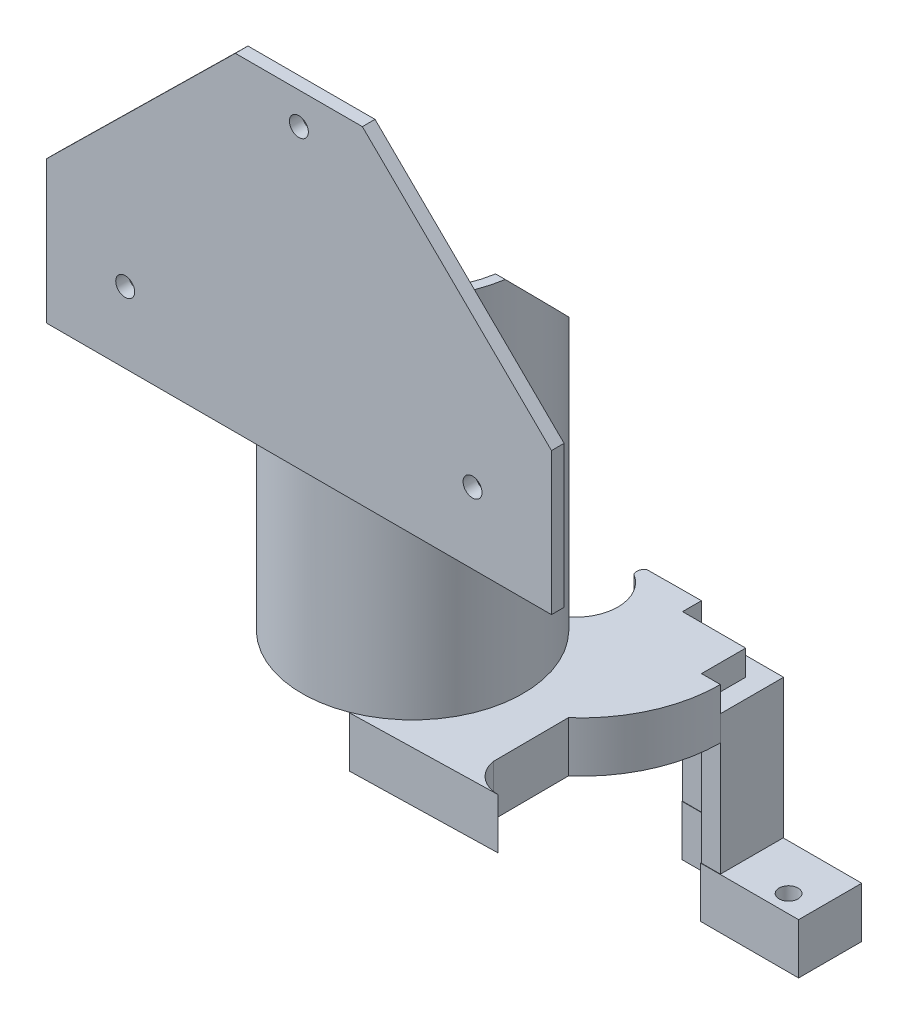
SolidWorks part; units mm, degrees
ref_plane "Front Plane" through (0, 0, 0) normal (0, 0, 1) x (1, 0, 0)
ref_plane "Top Plane" through (0, 0, 0) normal (0, 1, 0) x (1, 0, 0)
ref_plane "Right Plane" through (0, 0, 0) normal (1, 0, 0) x (0, 0, -1)
sketch "Sketch1" plane through (0, 0, 0) normal (0, 1, 0) x (1, 0, 0)
  circle A0 centre (0, 0) radius 17.5
  dimension "D1" = 35
extrude "Boss-Extrude1" add sketch "Sketch1" along normal blind 53 and the other way blind 5
sketch "Sketch2" plane through (0, 53, 0) normal (0, 1, 0) x (1, 0, 0)
  circle A0 centre (0, 0) radius 16
extrude "Cut-Extrude1" cut sketch "Sketch2" against normal blind 108
sketch "Sketch3" plane through (0, 53, 0) normal (0, 1, 0) x (1, 0, 0)
  line L1 (-12.5, 6) -> (12.5, 6)
  line L2 (-12.5, 6) -> (-12.5, 26)
  line L3 (-12.5, 26) -> (12.5, 26)
  line L4 (12.5, 6) -> (12.5, 26)
  line L5 (-12.5, 6) -> (12.5, 26) construction
  line L6 (-12.5, 26) -> (12.5, 6) construction
  circle A0 centre (0, 0) radius 16 construction
  point P0 (0, 16)
extrude "Cut-Extrude2" cut sketch "Sketch3" against normal blind 108
sketch "Sketch7" plane through (0, 0, 0) normal (1, 0, 0) x (0, 0, -1)
  line L0 (12.2474, 53) -> (12.2474, 38)
  line L1 (12.2474, -5) -> (12.2474, 53) construction
  line L2 (12.2474, 38) -> (-2.6263, 53)
  line L3 (12.2474, 53) -> (-17.5, 53) construction
  line L4 (-2.6263, 53) -> (12.2474, 53)
extrude "Cut-Extrude3" cut sketch "Sketch7" against normal blind 108 and the other way blind 108
ref_plane "Plane1" through (0, 0, 18) normal (0, 0, 1) x (1, 0, 0)
sketch "Sketch8" plane through (0, 0, 18) normal (0, 0, 1) x (1, 0, 0)
  line L1 (10.0571, 78.0232) -> (40, 48.5711)
  line L2 (40, 48.5711) -> (40, 26.0711)
  line L3 (40, 26.0711) -> (0, 26.0711)
  line L5 (0, -16.3611) -> (0, 16.3611) construction
  line L7 (-40, 26.0711) -> (0, 26.0711)
  line L8 (-40, 48.5711) -> (-40, 26.0711)
  line L9 (-10.0571, 78.0232) -> (-40, 48.5711)
  line L11 (-10.0571, 78.0232) -> (10.0571, 78.0232)
extrude "Boss-Extrude2" add sketch "Sketch8" against normal blind 2
sketch "Sketch10" plane through (0, 0, 16) normal (0, 0, -1) x (-1, 0, 0)
  line L0 (0, 53) -> (0, 73) construction
  line L1 (-17.5, 37.3211) -> (-27.5, 37.3211) construction
  line L2 (-17.5, 50.3514) -> (-17.5, -5) construction
  line L3 (17.5, 37.3211) -> (27.5, 37.3211) construction
  line L4 (17.5, -5) -> (17.5, 50.3514) construction
  circle A0 centre (-27.5, 37.3211) radius 1.5
  circle A1 centre (27.5, 37.3211) radius 1.5
  circle A2 centre (0, 73) radius 1.5
extrude "Cut-Extrude4" cut sketch "Sketch10" against normal blind 16
sketch "Sketch11" plane through (0, -5, 0) normal (0, -1, 0) x (1, 0, 0)
  line L0 (10.2759, -26.8054) -> (18.8909, -26.8634)
  line L1 (18.8909, -26.8634) -> (18.8909, -23.8634)
  line L2 (18.8909, -23.8634) -> (28.8909, -23.8634)
  line L3 (28.8909, -23.8634) -> (28.8909, -16.8634)
  line L4 (28.8909, -16.8634) -> (31.8909, -16.8634)
  line L5 (24.3909, -0.2751) -> (24.4524, 11.6188)
  line L6 (29.3909, 15.8366) -> (6.3756, 16.3864)
  line L7 (6.3756, 16.3864) -> (6.0124, 1.1829)
  line L8 (6.0124, 1.1829) -> (6.3909, -8.8634)
  line L9 (6.3909, -8.8634) -> (6.4802, -11.761)
  arc A0 (9.9319, -25.1296) -> (8.7246, -13.0297) centre (6.3756, -19.3742) ccw
  arc A1 (9.9319, -25.1296) -> (10.2759, -26.8054) centre (10.9418, -25.7955) ccw
  arc A2 (31.8909, -16.8634) -> (24.3909, -0.2751) centre (9.7961, -16.8634) ccw
  arc A3 (24.4524, 11.6188) -> (29.3909, 15.8366) centre (29.3908, 10.8366) cw
  arc A4 (6.4802, -11.761) -> (8.7246, -13.0297) centre (8.2368, -11.2731) ccw
extrude "Boss-Extrude3" add sketch "Sketch11" along normal blind 8
sketch "Sketch12" plane through (0, -13, 0) normal (0, -1, 0) x (1, 0, 0)
  line L10 (18.8909, -26.8634) -> (18.8909, -23.8634)
  line L11 (18.8909, -23.8634) -> (28.8909, -23.8634)
  line L12 (28.8909, -23.8634) -> (28.8909, -16.8634)
  line L13 (28.8909, -16.8634) -> (31.8909, -16.8634)
  line L14 (31.8909, -16.8634) -> (31.8909, -26.8634)
  line L15 (31.8909, -26.8634) -> (18.8909, -26.8634)
extrude "Boss-Extrude5" add sketch "Sketch12" along normal blind 18 and the other way blind 4 separate body
sketch "Sketch13" plane through (0, -31, 0) normal (0, -1, 0) x (1, 0, 0)
  line L0 (18.8227, -26.8076) -> (18.8227, -23.8076)
  line L1 (18.8227, -23.8076) -> (28.8227, -23.8076)
  line L2 (28.8227, -23.8076) -> (28.8227, -16.8076)
  line L3 (28.8227, -16.8076) -> (44.3227, -16.8076)
  line L4 (44.3227, -16.8076) -> (44.3227, -26.8076)
  line L5 (44.3227, -26.8076) -> (18.8227, -26.8076)
  circle A0 centre (39.936, -19.6077) radius 1.5002
extrude "Boss-Extrude6" add sketch "Sketch13" along normal blind 8
